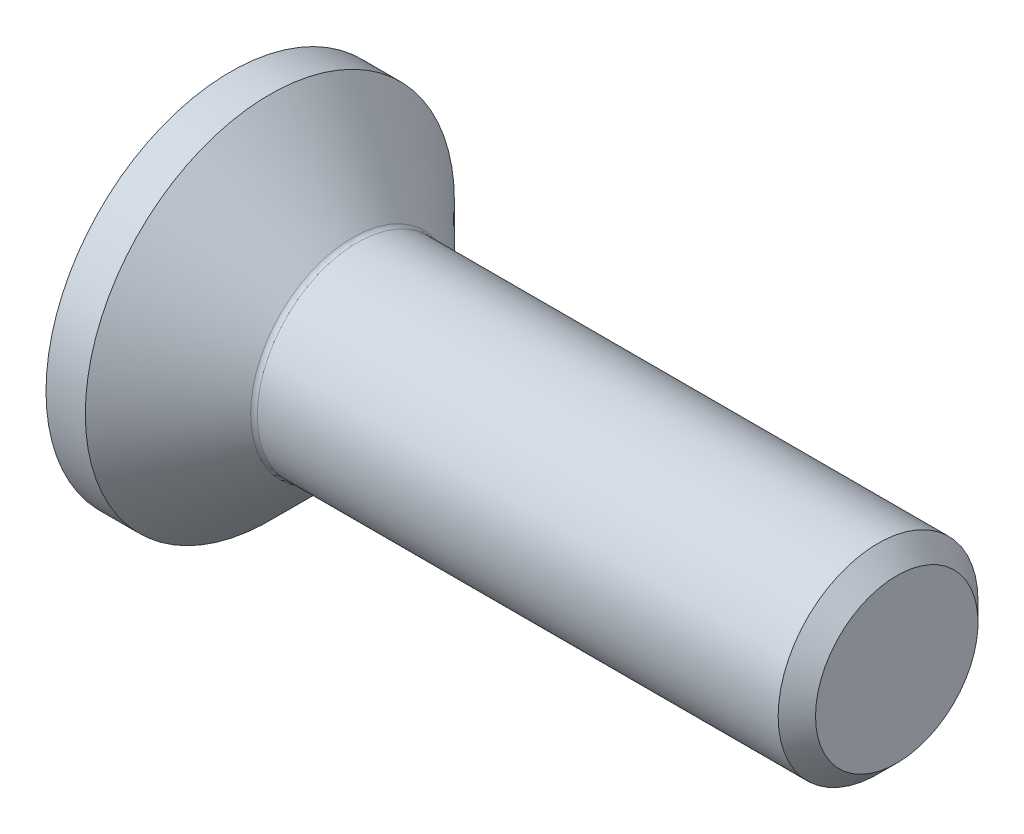
SolidWorks part; units mm, degrees
ref_plane "Plane1" through (0, 0, 0) normal (0, 0, 1) x (1, 0, 0)
ref_plane "Plane2" through (0, 0, 0) normal (0, 1, 0) x (1, 0, 0)
ref_plane "Plane3" through (0, 0, 0) normal (1, 0, 0) x (0, 0, -1)
sketch "BodySke" plane through (0, 0, 0) normal (0, 0, 1) x (1, 0, 0)
  line L0 (0, 0) -> (0, 2.77)
  line L1 (0.59, 2.77) -> (1.86, 1.5)
  line L2 (0, 2.77) -> (0.59, 2.77)
  line L3 (1.86, 1.5) -> (9.7195, 1.5)
  line L4 (10, 1.2195) -> (10, 0)
  line L5 (10, 0) -> (0, 0)
  line L6 (0, 0) -> (127, 0) construction
  line L7 (0.59, -2.77) -> (1.86, -1.5) construction
  line L8 (10, 1.2195) -> (9.7195, 1.5)
  line L9 (0, -2.77) -> (0.59, -2.77) construction
  line L10 (10, -1.2195) -> (9.7195, -1.5) construction
  line L11 (2.36, 7.85) -> (2.36, -14.375) construction
  line L12 (0, 19.05) -> (0, -3.175) construction
  dimension "D1" = 0.59
  dimension "Diameter" = 3
  dimension "Head_ht" = 1.86
  dimension "Length" = 10
  dimension "Body_ch_ang" = 45
  dimension "Head_dia" = 5.54
  dimension "Minor_dia" = 2.439
  dimension "Head_ang" = 90
  dimension "Advance" = 0.5
  dimension "Thread_nom" = 10
revolve "BaseBody" add sketch "BodySke"
cosmetic thread "ThreadCosmetic"
fillet "Fillet1" radius 0.1 1 edges at (1.86, 0, 1.5)
sketch "Sketch2" plane through (0, 0, 0) normal (0, 0, 1) x (1, 0, 0)
  line L0 (0, 1) -> (1.1, 1)
  line L1 (1.1, 1) -> (1.6774, 0)
  line L2 (0, 0) -> (127, 0) construction
  line L3 (1.6774, 0) -> (0, 0)
  line L4 (0, 0) -> (0, 1)
  line L5 (0, -1) -> (1.1, -1) construction
  line L6 (0, 0) -> (47.625, 0) construction
  line L8 (0, 2.77) -> (0, -2.77) construction
  dimension "D2" = 60
  dimension "PreBroach_depth" = 1.1
  dimension "PreBroach_dia" = 2
revolve "PreBroach" cut sketch "Sketch2" angle 360 about L6
sketch "Sketch3" plane through (0, 0, 0) normal (-1, 0, 0) x (0, 0, 1)
  line L0 (-1, -0.5774) -> (-1, 0.5774)
  line L1 (-1, 0.5774) -> (0, 1.1547)
  line L2 (0, 1.1547) -> (1, 0.5774)
  line L3 (1, 0.5774) -> (1, -0.5774)
  line L4 (1, -0.5774) -> (0, -1.1547)
  line L5 (0, -1.1547) -> (-1, -0.5774)
  dimension "D1" = 1
  dimension "D2" = 1
  dimension "D3" = 2
  dimension "Hex_size" = 2
extrude "Hex" cut sketch "Sketch3" against normal blind 1.1
sketch "ThdSchSke" plane through (0, 0, 0) normal (0, 0, 1) x (1, 0, 0)
  line L0 (3.36, -1.2195) -> (3.1636, -1.5)
  line L1 (3.36, -1.2195) -> (3.5564, -1.5)
  line L2 (3.5564, -1.5) -> (3.5564, -1.875)
  line L3 (-3.175, 0) -> (5.1513, 0) construction
  line L4 (0, 2.77) -> (0, -2.77) construction
  line L5 (3.5564, -1.875) -> (3.1636, -1.875)
  line L6 (3.1636, -1.875) -> (3.1636, -1.5)
  dimension "Thread_minor" = 2.439
  dimension "Diameter" = 3
  dimension "Start" = 3.36
  dimension "SideAngle" = 55
  dimension "VeeAngle" = 70
  dimension "Overcut" = 3.75
revolve "ThreadSchematic" [suppressed] cut sketch "ThdSchSke" angle 360 about L3
pattern_linear "ThdSchPat" [suppressed]
equation "\"Thread_minor@ThreadCosmetic\"  =  \"Minor_dia@BodySke\""
equation "\"D1@Sketch3\" = \"Hex_size@Sketch3\" / 2"
equation "\"D2@Sketch3\" = \"D1@Sketch3\""
equation "\"D3@Sketch3\" = \"Hex_size@Sketch3\""
equation "\"Thread_length@ThreadCosmetic\" = ((sgn( (\"Length@BodySke\" - \"Advance@BodySke\" * 3.0 - \"Head_ht@BodySke\" ) - \"Thread_nom@BodySke\" )-1)*( (\"Length@BodySke\" - \"Advance@BodySke\" * 3.0 - \"Head_ht@BodySke\" ) - \"Thread_nom@BodySke\" ))/-2+ \"Thread_nom@BodySke\""
equation "\"Thread_minor@ThdSchSke\" = \"Minor_dia@BodySke\""
equation "\"Diameter@ThdSchSke\" = \"Diameter@BodySke\""
equation "\"Overcut@ThdSchSke\" = \"Diameter@BodySke\" * 1.25"
equation "\"Start@ThdSchSke\" = 0.000001 + \"Length@BodySke\" - \"Thread_length@ThreadCosmetic\"  '---Countersunk---"
equation "\"Num_threads@ThdSchPat\" = int( \"Thread_length@ThreadCosmetic\" / \"Advance@BodySke\" + 0.999 )  + 1"
equation "\"Advance@ThdSchPat\" = \"Thread_length@ThreadCosmetic\" /  (\"Num_threads@ThdSchPat\" - 1) 'relax it"
equation "\"Num_threads@ThdSchPat\" = \"Num_threads@ThdSchPat\" - sgn( \"Num_threads@ThdSchPat\" - 1) '---chamfered tips only---"
